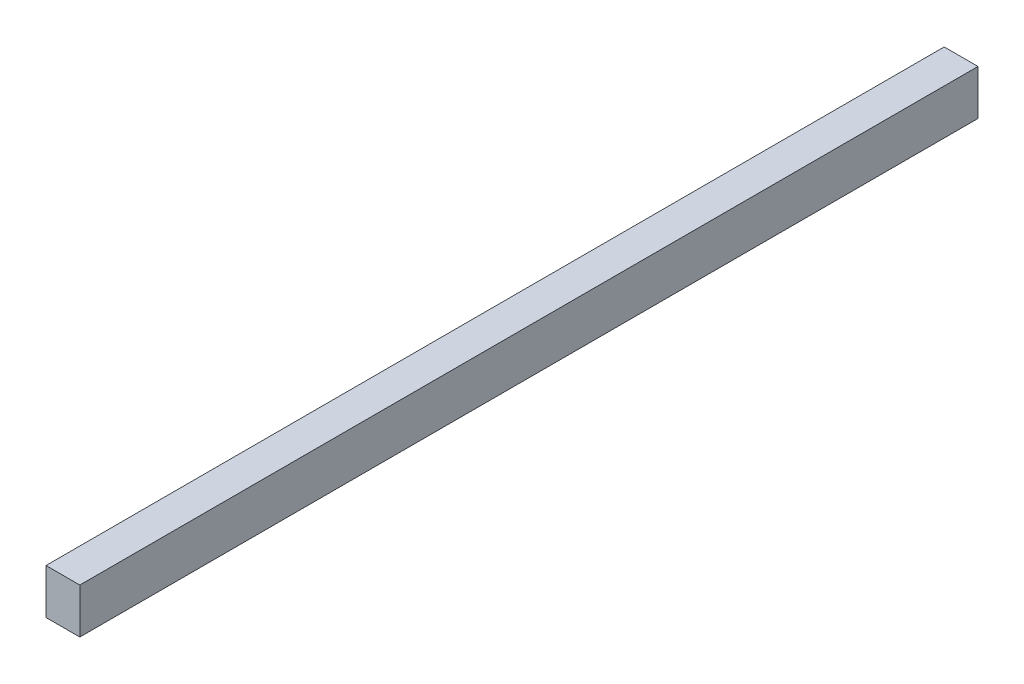
SolidWorks part; units mm, degrees
material "Beech"
ref_plane "Front Plane" through (0, 0, 0) normal (0, 0, 1) x (1, 0, 0)
ref_plane "Top Plane" through (0, 0, 0) normal (0, 1, 0) x (1, 0, 0)
ref_plane "Right Plane" through (0, 0, 0) normal (1, 0, 0) x (0, 0, -1)
sketch "Sketch1" plane through (0, 0, 0) normal (0, 0, 1) x (1, 0, 0)
  line L0 (-43.3027, 40) -> (-43.3027, 0)
  line L1 (-43.3027, 0) -> (-13.3027, 0)
  line L2 (-13.3027, 0) -> (-13.3027, 40)
  line L3 (-13.3027, 40) -> (-43.3027, 40)
extrude "Boss-Extrude1" add sketch "Sketch1" along normal blind 797
